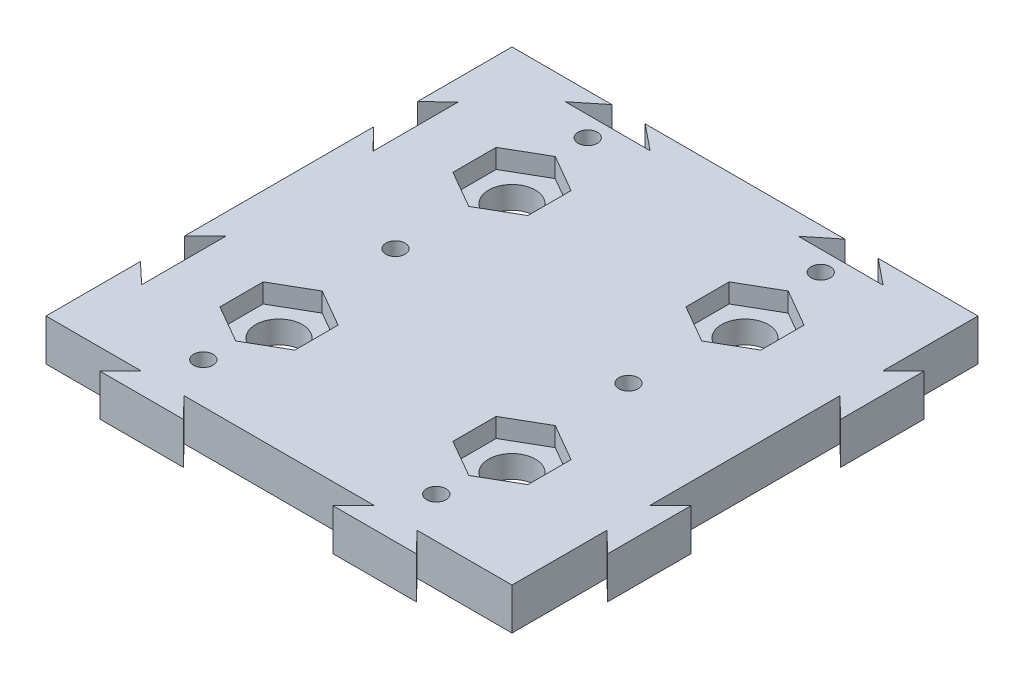
SolidWorks part; units mm, degrees
ref_plane "Front Plane" through (0, 0, 0) normal (0, 0, 1) x (1, 0, 0)
ref_plane "Top Plane" through (0, 0, 0) normal (0, 1, 0) x (1, 0, 0)
ref_plane "Right Plane" through (0, 0, 0) normal (1, 0, 0) x (0, 0, -1)
sketch "Sketch1" plane through (0, 0, 0) normal (0, 1, 0) x (1, 0, 0)
  line L1 (-17.78, -17.78) -> (17.78, -17.78)
  line L2 (-17.78, -17.78) -> (-17.78, 17.78)
  line L3 (-17.78, 17.78) -> (17.78, 17.78)
  line L4 (17.78, -17.78) -> (17.78, 17.78)
  line L5 (-17.78, -17.78) -> (17.78, 17.78) construction
  line L6 (-17.78, 17.78) -> (17.78, -17.78) construction
  point P0 (0, 0)
  dimension "D1" = 35.56
  dimension "D2" = 35.56
extrude "Boss-Extrude1" add sketch "Sketch1" along normal blind 6.35
sketch "Sketch2" plane through (0, 6.35, 0) normal (0, 1, 0) x (1, 0, 0)
  line L1 (0, 6.5991) -> (-5.715, 3.2996)
  line L2 (-5.715, 3.2996) -> (-5.715, -3.2996)
  line L3 (-5.715, -3.2996) -> (0, -6.5991)
  line L4 (0, -6.5991) -> (5.715, -3.2996)
  line L5 (5.715, -3.2996) -> (5.715, 3.2996)
  line L6 (5.715, 3.2996) -> (0, 6.5991)
  circle A0 centre (0, 0) radius 5.715 construction
  dimension "D1" = 11.43
extrude "Cut-Extrude1" cut sketch "Sketch2" against normal blind 2.921
hole_wizard "1/4 Clearance Hole1" positions "Sketch4" profile "Sketch3" hole size "1/4" standard "ANSI Inch"
sketch "Sketch4" plane through (0, 3.429, 0) normal (0, 1, 0) x (1, 0, 0)
  point P0 (0, 0)
sketch "Sketch3" plane through (0, 3.429, 0) normal (1, 0, 0) x (0, 0, 1)
  line L0 (0, 0) -> (0, 11.0358)
  line L1 (0, 11.0358) -> (3.5712, 8.89)
  line L2 (3.5712, 8.89) -> (3.5712, 0)
  line L5 (3.5712, 0) -> (0, 0)
  line L10 (0, 11.0358) -> (-3.5712, 8.89) construction
  line L11 (0, -6.35) -> (0, 107.95) construction
  dimension "Hole Dia." = 7.1425
  dimension "Hole Depth" = 8.89
  dimension "Drill Angle" = 118
pattern_linear "LPattern11" count 2 spacing 35.56 along (0, 0, 1) count 2 spacing 35.56 along (-1, 0, 0) of "Boss-Extrude1", "Cut-Extrude1", "1/4 Clearance Hole1"
hole_wizard "CBORE for #4 Socket Head Cap Screw5" positions "Sketch16" profile "Sketch15" counterbore size "#4" standard "ANSI Inch"
sketch "Sketch16" plane through (0, 0, 0) normal (0, -1, 0) x (-1, 0, 0)
  point P0 (0, 11.557)
  dimension "D1" = 11.557
sketch "Sketch15" plane through (0, 0, -11.557) normal (1, 0, 0) x (0, 0, -1)
  line L0 (0, 0) -> (0, 9.7752)
  line L1 (0, 9.7752) -> (1.4732, 8.89)
  line L2 (1.4732, 8.89) -> (1.4732, 3.81)
  line L3 (1.4732, 3.81) -> (2.794, 3.81)
  line L4 (2.794, 3.81) -> (2.794, 0)
  line L5 (2.794, 0) -> (0, 0)
  line L10 (0, 9.7752) -> (-1.4732, 8.89) construction
  line L11 (0, -6.35) -> (0, 107.95) construction
  dimension "Hole Dia." = 2.9464
  dimension "Hole Depth" = 8.89
  dimension "C'Bore Dia." = 5.588
  dimension "C'Bore Depth" = 3.81
  dimension "Drill Angle" = 118
pattern_linear "LPattern15" count 2 spacing 35.56 along (-1, 0, 0) of "CBORE for #4 Socket Head Cap Screw5"
hole_wizard "CBORE for #4 Socket Head Cap Screw6" positions "Sketch18" profile "Sketch17" counterbore size "#4" standard "ANSI Inch"
sketch "Sketch18" plane through (0, 0, 0) normal (0, -1, 0) x (-1, 0, 0)
  point P0 (0, -17.78)
  dimension "D1" = 17.78
sketch "Sketch17" plane through (0, 0, 17.78) normal (1, 0, 0) x (0, 0, -1)
  line L0 (0, 0) -> (0, 9.7752)
  line L1 (0, 9.7752) -> (1.4732, 8.89)
  line L2 (1.4732, 8.89) -> (1.4732, 3.81)
  line L3 (1.4732, 3.81) -> (2.794, 3.81)
  line L4 (2.794, 3.81) -> (2.794, 0)
  line L5 (2.794, 0) -> (0, 0)
  line L10 (0, 9.7752) -> (-1.4732, 8.89) construction
  line L11 (0, -6.35) -> (0, 107.95) construction
  dimension "Hole Dia." = 2.9464
  dimension "Hole Depth" = 8.89
  dimension "C'Bore Dia." = 5.588
  dimension "C'Bore Depth" = 3.81
  dimension "Drill Angle" = 118
pattern_linear "LPattern16" count 2 spacing 35.56 along (-1, 0, 0) of "CBORE for #4 Socket Head Cap Screw6"
ref_plane "Plane1" through (0, 0, 17.78) normal (0, 0, 1) x (1, 0, 0)
mirror "Mirror1" about plane through (0, 0, 17.78) normal (0, 0, 1) of "LPattern15", "CBORE for #4 Socket Head Cap Screw5"
sketch "Sketch20" plane through (0, 0, 0) normal (0, 1, 0) x (1, 0, 0)
  line L1 (17.78, -53.34) -> (17.78, 17.78) construction
  line L2 (17.78, 6.35) -> (20.955, 6.35)
  line L3 (17.78, 6.35) -> (17.78, -6.35)
  line L4 (17.78, -6.35) -> (20.955, -6.35)
  line L5 (20.955, 6.35) -> (20.955, -6.35)
  line L7 (17.78, -29.21) -> (20.955, -29.21)
  line L8 (17.78, -29.21) -> (17.78, -41.91)
  line L9 (17.78, -41.91) -> (20.955, -41.91)
  line L10 (20.955, -29.21) -> (20.955, -41.91)
  dimension "D1" = 6.35
  dimension "D2" = 12.7
  dimension "D3" = 3.175
  dimension ".125" = 3.175
  dimension "D5" = 12.7
  dimension "D6" = 6.35
extrude "Boss-Extrude2" add sketch "Sketch20" along normal up to surface (6.35 mm away) up to face at (-35.56, 6.35, 45.6438)
sketch "Sketch21" plane through (0, 6.35, 0) normal (0, 1, 0) x (1, 0, 0)
  line L0 (20.955, -6.35) -> (17.78, -6.35)
  line L1 (17.78, -6.35) -> (17.78, -3.302)
  line L2 (17.78, -3.302) -> (20.955, -6.35)
  line L3 (20.955, 6.35) -> (17.78, 6.35)
  line L4 (17.78, 6.35) -> (17.78, 3.302)
  line L5 (17.78, 3.302) -> (20.955, 6.35)
  line L6 (20.955, -29.21) -> (17.78, -29.21)
  line L7 (17.78, -29.21) -> (17.78, -32.258)
  line L8 (17.78, -32.258) -> (20.955, -29.21)
  line L9 (20.955, -41.91) -> (17.78, -41.91)
  line L10 (17.78, -41.91) -> (17.78, -38.862)
  line L11 (17.78, -38.862) -> (20.955, -41.91)
  dimension "D1" = 3.048
  dimension "D2" = 3.048
  dimension "D3" = 3.048
  dimension "D4" = 3.048
extrude "Cut-Extrude2" cut sketch "Sketch21" against normal through all
sketch "Sketch22" plane through (0, 0, 0) normal (0, 1, 0) x (1, 0, 0)
  line L0 (-53.34, -53.34) -> (17.78, -53.34) construction
  line L1 (-41.91, -53.34) -> (-29.21, -53.34)
  line L2 (-41.91, -53.34) -> (-41.91, -56.515)
  line L3 (-41.91, -56.515) -> (-29.21, -56.515)
  line L4 (-29.21, -53.34) -> (-29.21, -56.515)
  line L6 (-6.35, -53.34) -> (6.35, -53.34)
  line L7 (-6.35, -53.34) -> (-6.35, -56.515)
  line L8 (-6.35, -56.515) -> (6.35, -56.515)
  line L9 (6.35, -53.34) -> (6.35, -56.515)
  dimension "D1" = 12.7
  dimension "D2" = 12.7
  dimension "D3" = 6.35
  dimension "D4" = 6.35
  dimension "D5" = 3.175
  dimension "D6" = 3.175
extrude "Boss-Extrude3" add sketch "Sketch22" along normal up to surface (6.35 mm away) up to face at (-35.56, 6.35, 45.6438)
sketch "Sketch23" plane through (0, 6.35, 0) normal (0, 1, 0) x (1, 0, 0)
  line L0 (-41.91, -56.515) -> (-41.91, -53.34)
  line L1 (-41.91, -53.34) -> (-38.862, -53.34)
  line L2 (-38.862, -53.34) -> (-41.91, -56.515)
  line L3 (-29.21, -56.515) -> (-29.21, -53.34)
  line L4 (-29.21, -53.34) -> (-32.258, -53.34)
  line L5 (-32.258, -53.34) -> (-29.21, -56.515)
  line L6 (-6.35, -56.515) -> (-6.35, -53.34)
  line L7 (-6.35, -53.34) -> (-3.302, -53.34)
  line L8 (-3.302, -53.34) -> (-6.35, -56.515)
  line L9 (6.35, -56.515) -> (6.35, -53.34)
  line L10 (6.35, -53.34) -> (3.302, -53.34)
  line L11 (3.302, -53.34) -> (6.35, -56.515)
  dimension "D1" = 3.048
  dimension "D2" = 3.048
  dimension "D3" = 3.048
  dimension "D4" = 3.048
extrude "Cut-Extrude3" cut sketch "Sketch23" against normal through all
sketch "Sketch24" plane through (0, 6.35, 0) normal (0, 1, 0) x (1, 0, 0)
  line L0 (-53.34, 3.3655) -> (-53.34, -3.3655)
  line L2 (-53.34, 17.78) -> (-53.34, -53.34) construction
  line L3 (-53.34, -3.3655) -> (-50.165, -6.5913)
  line L4 (-50.165, -6.5913) -> (-50.165, 6.3627)
  line L5 (-50.165, 6.3627) -> (-53.34, 3.3655)
  dimension "D1" = 12.954
  dimension "D2" = 6.3627
  dimension "D3" = 3.175
  dimension "D4" = 6.731
  dimension "D5" = 3.3655
extrude "Cut-Extrude4" cut sketch "Sketch24" against normal through all
mirror "Mirror2" about plane through (0, 0, 17.78) normal (0, 0, 1) of "Cut-Extrude4"
sketch "Sketch25" plane through (0, 6.35, 0) normal (0, 1, 0) x (1, 0, 0)
  line L0 (-38.1, 17.78) -> (-33.02, 17.78)
  line L1 (17.78, 17.78) -> (-53.34, 17.78) construction
  line L2 (-33.02, 17.78) -> (-29.083, 14.605)
  line L3 (-29.083, 14.605) -> (-42.037, 14.605)
  line L4 (-42.037, 14.605) -> (-38.1, 17.78)
  line L5 (-2.54, 17.78) -> (2.54, 17.78)
  line L6 (2.54, 17.78) -> (6.477, 14.605)
  line L7 (6.477, 14.605) -> (-6.477, 14.605)
  line L8 (-6.477, 14.605) -> (-2.54, 17.78)
  dimension "D1" = 3.175
  dimension "D2" = 5.08
  dimension "D3" = 12.954
  dimension "D4" = 6.477
  dimension "D5" = 2.54
  dimension "D6" = 12.954
  dimension "D7" = 5.08
  dimension "D8" = 2.54
  dimension "D9" = 3.175
extrude "Cut-Extrude5" cut sketch "Sketch25" against normal through all
